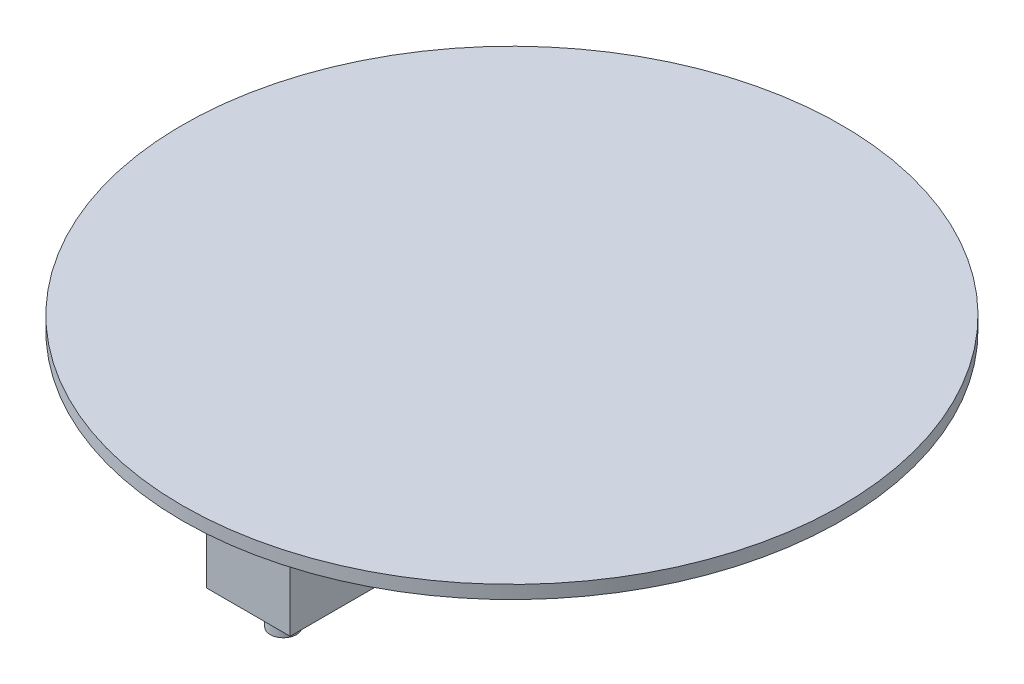
SolidWorks part; units mm, degrees
ref_plane "Front Plane" through (0, 0, 0) normal (0, 0, 1) x (1, 0, 0)
ref_plane "Top Plane" through (0, 0, 0) normal (0, 1, 0) x (1, 0, 0)
ref_plane "Right Plane" through (0, 0, 0) normal (1, 0, 0) x (0, 0, -1)
sketch "Sketch1" plane through (0, 0, 0) normal (0, 0, 1) x (1, 0, 0)
  line L1 (0, 0) -> (12.7, 0)
  line L2 (0, 0) -> (0, 12.7)
  line L3 (0, 12.7) -> (12.7, 12.7)
  line L4 (12.7, 0) -> (12.7, 12.7)
  dimension "D1" = 12.7
extrude "Boss-Extrude1" add sketch "Sketch1" along normal blind 80
sketch "Sketch2" plane through (0, 12.7, 0) normal (0, 1, 0) x (1, 0, 0)
  line L0 (12.7, 0) -> (0, 0) construction
  circle A0 centre (6.6687, -5) radius 2
  circle A1 centre (6.6687, -20) radius 2
  circle A2 centre (6.6687, -60) radius 2
  circle A3 centre (6.6687, -75) radius 2
  dimension "D1" = 4
  dimension "D2" = 5
  dimension "D3" = 15
  dimension "D4" = 40
  dimension "D5" = 15
extrude "Cut-Extrude1" cut sketch "Sketch2" against normal through all
sketch "Sketch4" plane through (0, 0, 0) normal (-1, 0, 0) x (0, 0, 1)
  line L0 (40, 0) -> (40, 12.7) construction
  line L1 (80, 0) -> (0, 0) construction
  line L2 (80, 12.7) -> (0, 12.7) construction
  line L3 (-1.1232, 205.6227) -> (294.8768, 205.6227) construction
  arc A0 (40, 2.7275) -> (40, 9.9725) centre (43.8, 6.35) ccw
  arc A1 (40, 9.9725) -> (40, 2.7275) centre (36.2, 6.35) ccw
  point P13 (40, 6.35)
  dimension "D1" = 10.5
  dimension "D3" = 10.5
  dimension "D4" = 3.8
extrude "Cut-Extrude2" cut sketch "Sketch4" against normal through all
sketch "Sketch5" plane through (0, 0, 0) normal (0, 1, 0) x (1, 0, 0)
  circle A0 centre (6.6687, -20) radius 2 construction
  circle A1 centre (6.6687, -5) radius 2 construction
  circle A2 centre (6.6687, -20) radius 2
  circle A3 centre (6.6687, -5) radius 2
extrude "Boss-Extrude2" add sketch "Sketch5" along normal blind 17
sketch "Sketch6" plane through (0, 12.7, 0) normal (0, 1, 0) x (1, 0, 0)
  circle A0 centre (6.6687, -75) radius 2 construction
  circle A1 centre (6.6687, -60) radius 2 construction
  circle A2 centre (6.6687, -75) radius 2
  circle A3 centre (6.6687, -60) radius 2
extrude "Boss-Extrude3" add sketch "Sketch6" against normal blind 17
sketch "Sketch7" plane through (0, 17, 0) normal (0, 1, 0) x (1, 0, 0)
  circle A0 centre (6.35, -40) radius 50
  dimension "D1" = 100
extrude "Boss-Extrude4" add sketch "Sketch7" along normal blind 2
